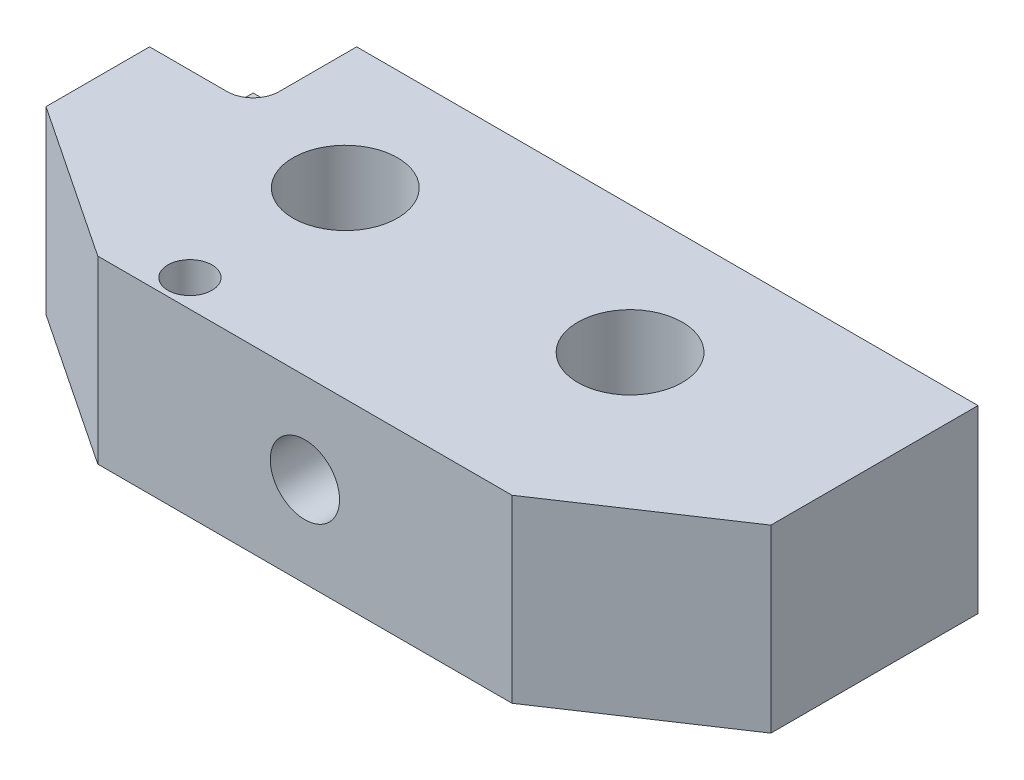
SolidWorks part; units mm, degrees
material "6061-T6 (SS)"
ref_plane "Front Plane" through (0, 0, 0) normal (0, 0, 1) x (1, 0, 0)
ref_plane "Top Plane" through (0, 0, 0) normal (0, 1, 0) x (1, 0, 0)
ref_plane "Right Plane" through (0, 0, 0) normal (1, 0, 0) x (0, 0, -1)
sketch "Sketch1" plane through (0, 0, 0) normal (0, 1, 0) x (1, 0, 0)
  line L0 (-44.45, -6.35) -> (-25.4, -19.05)
  line L1 (-25.4, -19.05) -> (25.4, -19.05)
  line L2 (-44.45, -6.35) -> (-44.45, 19.05)
  line L3 (-44.45, 19.05) -> (44.45, 19.05)
  line L4 (44.45, -6.35) -> (44.45, 19.05)
  line L5 (44.45, -6.35) -> (25.4, -19.05)
  line L6 (-44.45, 0) -> (44.45, 0) construction
  line L7 (0, 19.05) -> (0, -19.05) construction
  point P0 (0, 0)
  dimension "D1" = 88.9
  dimension "D2" = 38.1
  dimension "D3" = 12.7
  dimension "D4" = 19.05
  dimension "D5" = 19.05
extrude "Boss-Extrude1" add sketch "Sketch1" along normal blind 22.098
sketch "Sketch2" plane through (0, 22.098, 0) normal (0, 1, 0) x (1, 0, 0)
  line L0 (-31.75, 19.05) -> (-31.75, 9.525)
  line L1 (44.45, 19.05) -> (-44.45, 19.05) construction
  line L2 (-34.925, 6.35) -> (-44.45, 6.35)
  line L3 (-44.45, 19.05) -> (-44.45, -6.35) construction
  line L4 (-44.45, 6.35) -> (-44.45, 19.05)
  line L5 (-44.45, 19.05) -> (-31.75, 19.05)
  arc A0 (-31.75, 9.525) -> (-34.925, 6.35) centre (-34.925, 9.525) cw
  dimension "D3" = 3.175
  dimension "D1" = 12.7
  dimension "D2" = 12.7
extrude "Cut-Extrude1" cut sketch "Sketch2" against normal blind 11.2522
sketch "Sketch4" plane through (0, 0, 19.05) normal (0, 0, 1) x (1, 0, 0)
  line L0 (0, 22.098) -> (0, 0) construction
  line L1 (-25.4, 22.098) -> (25.4, 22.098) construction
  line L3 (-25.4, 22.098) -> (-25.4, 0) construction
  line L4 (-25.4, 11.049) -> (25.4, 11.049) construction
  line L5 (25.4, 22.098) -> (25.4, 0) construction
  point P13 (0, 11.049)
hole_wizard "M10x1.5 Tapped Hole1" positions "Sketch4" profile "Sketch5" tap size "M10x1.5" standard "ANSI Metric" end condition through all
sketch "Sketch5" plane through (0, 11.049, 19.05) normal (1, 0, 0) x (0, -1, 0)
  line L0 (0, 0) -> (0, 38.1)
  line L1 (0, 38.1) -> (4.25, 38.1)
  line L2 (4.25, 38.1) -> (4.25, 0)
  line L5 (4.25, 0) -> (0, 0)
  line L11 (0, -6.35) -> (0, 107.95) construction
  dimension "Thru Tap Drill Dia." = 8.5
  dimension "Thru Tap Drill Depth" = 38.1
cosmetic thread "Hole Thread1" parameters "D2"=10
sketch "Sketch6" plane through (0, 22.098, 0) normal (0, 1, 0) x (1, 0, 0)
  line L1 (0, 19.05) -> (0, -19.05) construction
  line L2 (44.45, 19.05) -> (-31.75, 19.05) construction
  line L3 (-25.4, -19.05) -> (25.4, -19.05) construction
  circle A0 centre (-17.4625, 3.3645) radius 6.4135
  circle A1 centre (17.4625, 3.3645) radius 6.4135
  dimension "D1" = 12.827
  dimension "D2" = 34.925
extrude "Cut-Extrude2" cut sketch "Sketch6" against normal through all
sketch "Sketch7" plane through (0, 0, 0) normal (0, -1, 0) x (1, 0, 0)
  line L2 (-17.4625, -3.3645) -> (-17.4625, 19.05) construction
  line L3 (-25.4, 19.05) -> (25.4, 19.05) construction
  circle A0 centre (17.4625, -3.3645) radius 6.4135 construction
  point P0 (-17.4625, 15.6855)
  point P16 (0, 0)
  dimension "D1" = 19.05
hole_wizard "1/4-28 Tapped Hole1" positions "Sketch7" profile "Sketch8" tap size "1/4-28" standard "ANSI Inch" end condition through all
cosmetic thread "Hole Thread2" parameters "D2"=6.35
sketch "Sketch8" plane through (-17.4625, 0, 15.6855) normal (1, 0, 0) x (0, 0, -1)
  line L0 (0, 0) -> (0, 22.098)
  line L1 (0, 22.098) -> (2.7051, 22.098)
  line L2 (2.7051, 22.098) -> (2.7051, 0)
  line L5 (2.7051, 0) -> (0, 0)
  line L11 (0, -6.35) -> (0, 107.95) construction
  dimension "Thru Tap Drill Dia." = 5.4102
  dimension "Thru Tap Drill Depth" = 22.098
